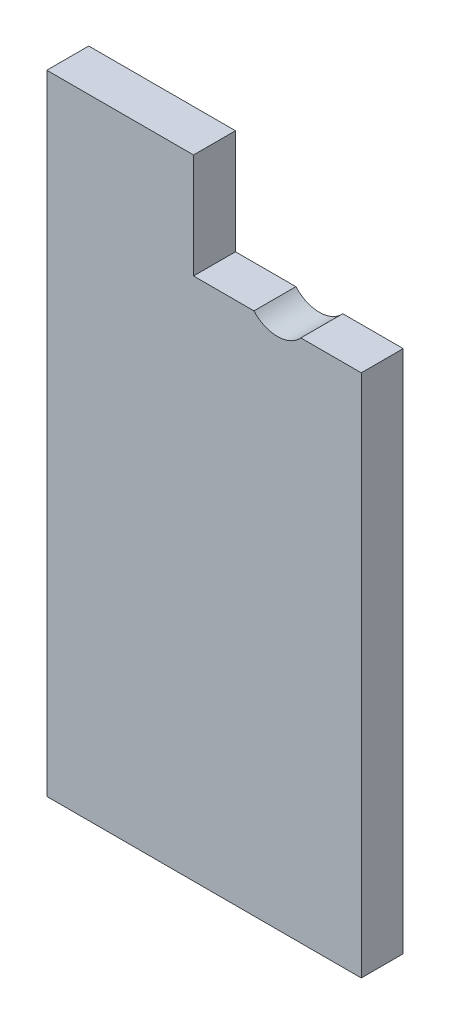
SolidWorks part; units mm, degrees
ref_plane "Front Plane" through (0, 0, 0) normal (0, 0, 1) x (1, 0, 0)
ref_plane "Top Plane" through (0, 0, 0) normal (0, 1, 0) x (1, 0, 0)
ref_plane "Right Plane" through (0, 0, 0) normal (1, 0, 0) x (0, 0, -1)
sketch "Sketch1" plane through (0, 0, 0) normal (0, 0, 1) x (1, 0, 0)
  line L0 (15, 25) -> (12.118, 25)
  line L1 (0, 0) -> (15, 0)
  line L2 (0, 0) -> (0, 30)
  line L3 (0, 30) -> (7, 30)
  line L4 (15, 0) -> (15, 25)
  line L5 (7, 30) -> (7, 25)
  line L8 (9.882, 25) -> (7, 25)
  arc A4 (9.882, 25) -> (12.118, 25) centre (11, 26) ccw
extrude "Boss-Extrude1" add sketch "Sketch1" along normal blind 2
